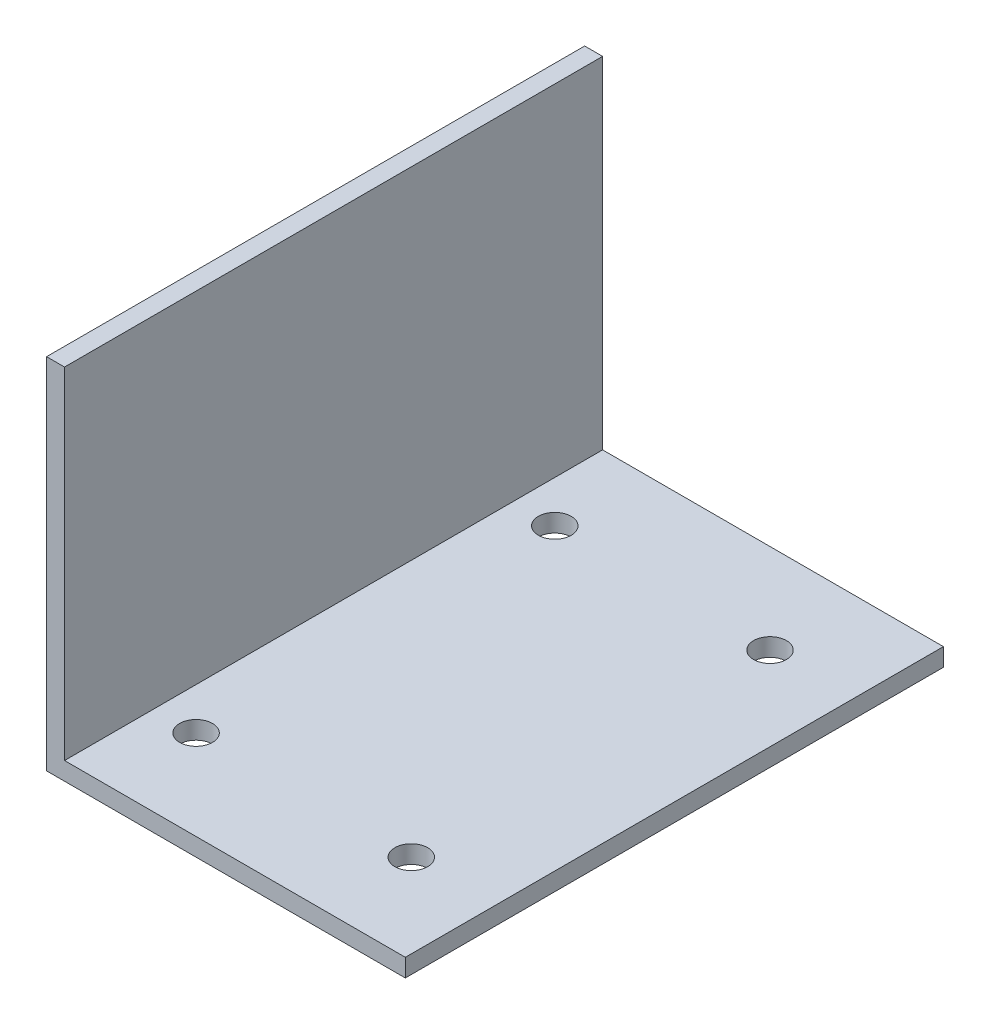
SolidWorks part; units mm, degrees
material "Д16Т ГОСТ 4784-74"
ref_plane "Спереди" through (0, 0, 0) normal (0, 0, 1) x (1, 0, 0)
ref_plane "Сверху" through (0, 0, 0) normal (0, 1, 0) x (1, 0, 0)
ref_plane "Справа" through (0, 0, 0) normal (1, 0, 0) x (0, 0, -1)
sketch "Эскиз1" plane through (0, 0, 0) normal (0, 0, 1) x (1, 0, 0)
  line L0 (0, 0) -> (0, 60)
  line L1 (0, 60) -> (3, 60)
  line L2 (3, 60) -> (3, 3)
  line L3 (3, 3) -> (60, 3)
  line L4 (60, 3) -> (60, 0)
  line L5 (60, 0) -> (0, 0)
  dimension "D1" = 60
  dimension "D2" = 60
  dimension "D3" = 3
extrude "Бобышка-Вытянуть1" add sketch "Эскиз1" along normal blind 90
sketch "Эскиз2" plane through (0, 0, 0) normal (0, -1, 0) x (1, 0, 0)
  line L0 (28, 75) -> (28, 15) construction
  line L1 (60, 45) -> (0, 45) construction
  line L2 (60, 90) -> (60, 0) construction
  line L3 (0, 90) -> (0, 0) construction
  line L4 (10, 75) -> (46, 75) construction
  line L5 (10, 15) -> (46, 15) construction
  circle A0 centre (10, 75) radius 2.75
  circle A1 centre (46, 75) radius 2.75
  circle A2 centre (46, 15) radius 2.75
  circle A3 centre (10, 15) radius 2.75
  dimension "D4" = 5.5
  dimension "D1" = 28
  dimension "D2" = 36
  dimension "D3" = 60
extrude "Вырез-Вытянуть1" cut sketch "Эскиз2" against normal through all
